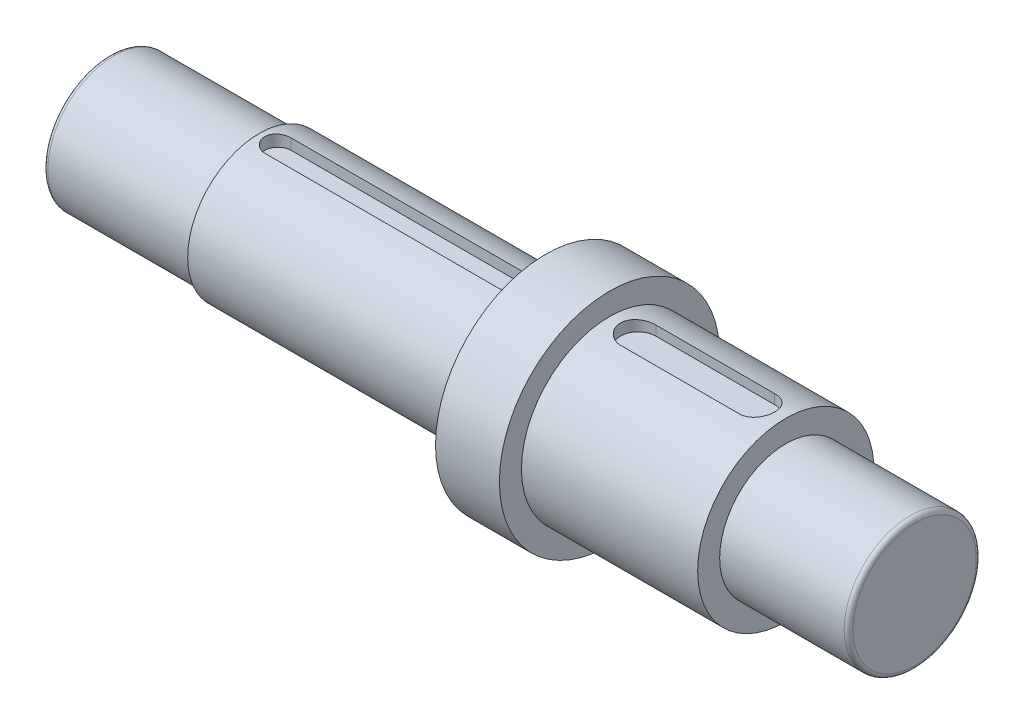
SolidWorks part; units mm, degrees
material "Plain Carbon Steel"
ref_plane "Front Plane" through (0, 0, 0) normal (0, 0, 1) x (1, 0, 0)
ref_plane "Top Plane" through (0, 0, 0) normal (0, 1, 0) x (1, 0, 0)
ref_plane "Right Plane" through (0, 0, 0) normal (1, 0, 0) x (0, 0, -1)
sketch "Sketch1" plane through (0, 0, 0) normal (0, 0, 1) x (1, 0, 0)
  line L0 (-188.0996, 0) -> (177.4004, 0) construction
  line L1 (-188.0996, 0) -> (-188.0996, 30)
  line L2 (-188.0996, 30) -> (-120.0996, 30)
  line L3 (-120.0996, 30) -> (-120.0996, 32.5)
  line L4 (-120.0996, 32.5) -> (9.9004, 32.5)
  line L5 (9.9004, 32.5) -> (9.9004, 50)
  line L6 (9.9004, 50) -> (38.9004, 50)
  line L7 (38.9004, 50) -> (38.9004, 40)
  line L8 (38.9004, 40) -> (118.9004, 40)
  line L9 (118.9004, 40) -> (118.9004, 30)
  line L10 (118.9004, 30) -> (177.4004, 30)
  line L11 (177.4004, 30) -> (177.4004, 0)
  line L12 (-188.0996, 0) -> (177.4004, 0)
  dimension "D1" = 365.5
  dimension "D2" = 68
  dimension "D3" = 130
  dimension "D4" = 29
  dimension "D5" = 80
  dimension "D6" = 60
  dimension "D7" = 65
  dimension "D8" = 100
  dimension "D9" = 80
  dimension "D10" = 60
revolve "Revolve1" add sketch "Sketch1" angle 360 about L0
fillet "Fillet1" radius 2 2 edges at (177.4004, 0, 30) (-188.0996, 0, 30)
ref_plane "Plane1" through (0, 32.5, 0) normal (0, 1, 0) x (1, 0, 0)
ref_plane "Plane2" through (0, 40, 0) normal (0, 1, 0) x (1, 0, 0)
sketch "Sketch2" plane through (0, 32.5, 0) normal (0, 1, 0) x (1, 0, 0)
  line L0 (-111.5996, 0) -> (1.4004, 0) construction
  line L1 (-111.5996, 6) -> (1.4004, 6)
  line L2 (-111.5996, -6) -> (1.4004, -6)
  line L3 (-120.0996, 32.5) -> (-120.0996, -32.5) construction
  arc A0 (-111.5996, 6) -> (-111.5996, -6) centre (-111.5996, 0) ccw
  arc A1 (1.4004, -6) -> (1.4004, 6) centre (1.4004, 0) ccw
  point P3 (-55.0996, 0)
  dimension "D2" = 6
  dimension "D1" = 113
  dimension "D3" = 65
extrude "Cut-Extrude1" cut sketch "Sketch2" against normal blind 5.44
sketch "Sketch3" plane through (0, 40, 0) normal (0, 1, 0) x (1, 0, 0)
  line L0 (51.9004, 0) -> (105.9004, 0) construction
  line L1 (51.9004, 8) -> (105.9004, 8)
  line L2 (51.9004, -8) -> (105.9004, -8)
  line L3 (118.9004, -40) -> (118.9004, 40) construction
  arc A0 (51.9004, 8) -> (51.9004, -8) centre (51.9004, 0) ccw
  arc A1 (105.9004, -8) -> (105.9004, 8) centre (105.9004, 0) ccw
  point P3 (78.9004, 0)
  dimension "D3" = 8
  dimension "D1" = 54
  dimension "D2" = 40
extrude "Cut-Extrude2" cut sketch "Sketch3" against normal blind 5.19
